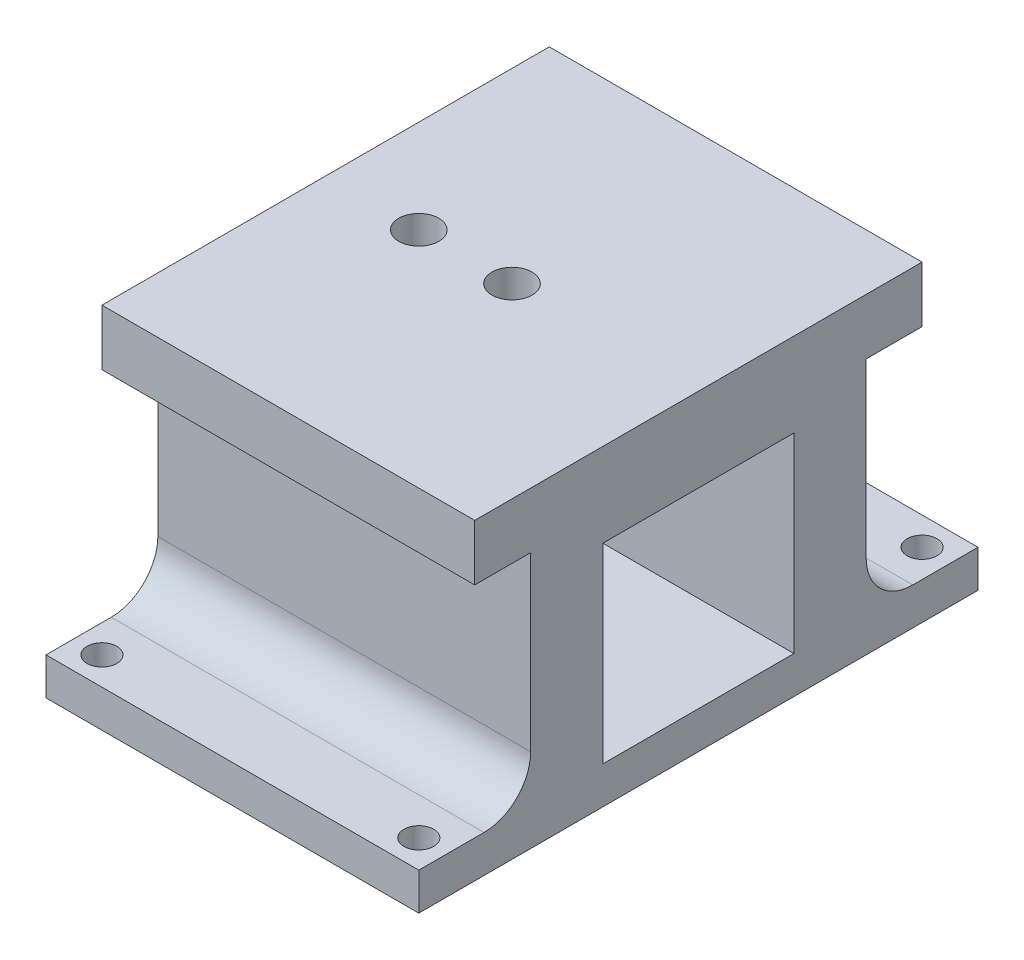
SolidWorks part; units mm, degrees
ref_plane "前视基准面" through (0, 0, 0) normal (0, 0, 1) x (1, 0, 0)
ref_plane "上视基准面" through (0, 0, 0) normal (0, 1, 0) x (1, 0, 0)
ref_plane "右视基准面" through (0, 0, 0) normal (1, 0, 0) x (0, 0, -1)
other "Configuration Table"
sketch "草图1" plane through (0, 0, 0) normal (0, 1, 0) x (1, 0, 0)
  line L0 (0, 0) -> (0, 14)
  line L1 (-20, -24) -> (20, -24)
  line L2 (-20, -24) -> (-20, 24)
  line L3 (-20, 24) -> (20, 24)
  line L4 (20, -24) -> (20, 24)
  line L5 (-20, -24) -> (20, 24) construction
  line L6 (-20, 24) -> (20, -24) construction
  line L7 (0, 14) -> (11.45, 14)
  line L8 (0, 0) -> (10.1755, 0)
  line L9 (0, 0) -> (0, -15.5)
  line L10 (0, -15.5) -> (0, 15.5) construction
  line L11 (-2.45, -15.5) -> (-2.45, 15.5)
  line L12 (2.45, -15.5) -> (2.45, 15.5)
  circle A0 centre (11.45, 14) radius 1.75
  circle A1 centre (-11.45, 14) radius 1.75
  circle A2 centre (-11.45, -14) radius 1.75
  circle A3 centre (11.45, -14) radius 1.75
  arc A4 (-2.45, -15.5) -> (2.45, -15.5) centre (0, -15.5) ccw
  arc A5 (2.45, 15.5) -> (-2.45, 15.5) centre (0, 15.5) ccw
  point P0 (0, 0)
  point P17 (0, 0)
  dimension "D5" = 3.5
  dimension "D8" = 2.45
  dimension "D1" = 48
  dimension "D2" = 40
  dimension "D3" = 14
  dimension "D4" = 11.45
  dimension "D6" = 15.5
  dimension "D7" = 31
extrude "凸台-拉伸1" add sketch "草图1" along normal blind 4
sketch "草图2" plane through (0, 4, 0) normal (0, 1, 0) x (1, 0, 0)
  line L0 (20, -24) -> (20, 24) construction
  line L1 (-20, -10.25) -> (20, -10.25)
  line L2 (-20, -10.25) -> (-20, 10.25)
  line L3 (-20, 10.25) -> (20, 10.25)
  line L4 (20, -10.25) -> (20, 10.25)
  line L5 (-20, -10.25) -> (20, 10.25) construction
  line L6 (-20, 10.25) -> (20, -10.25) construction
  line L8 (-20, -18) -> (20, -18)
  line L9 (-20, -18) -> (-20, 18)
  line L10 (-20, 18) -> (20, 18)
  line L11 (20, -18) -> (20, 18)
  line L12 (-20, -18) -> (20, 18) construction
  line L13 (-20, 18) -> (20, -18) construction
  point P0 (0, 0)
  point P8 (0, 0)
  dimension "D1" = 20.5
  dimension "D2" = 36
extrude "凸台-拉伸5" add sketch "草图2" along normal blind 20.5
sketch "草图4" plane through (0, 24.5, 0) normal (0, 1, 0) x (1, 0, 0)
  line L1 (-20, 18) -> (20, 18)
  line L2 (-20, 18) -> (-20, -18)
  line L3 (-20, -18) -> (20, -18)
  line L4 (20, 18) -> (20, -18)
extrude "凸台-拉伸6" add sketch "草图4" along normal blind 3
fillet "圆角4" radius 5 1 edges at (0, 4, -18)
fillet "圆角11" radius 5 1 edges at (0, 4, 18)
sketch "草图8" plane through (0, 27.5, 0) normal (0, 1, 0) x (1, 0, 0)
  line L1 (-20, 24) -> (20, 24)
  line L2 (-20, 24) -> (-20, -24)
  line L3 (-20, -24) -> (20, -24)
  line L4 (20, 24) -> (20, -24)
extrude "凸台-拉伸8" add sketch "草图8" along normal blind 4
sketch "草图9" plane through (0, 0, 0) normal (0, -1, 0) x (1, 0, 0)
  line L1 (-20, -30) -> (20, -30)
  line L2 (-20, -30) -> (-20, 30)
  line L3 (-20, 30) -> (20, 30)
  line L4 (20, -30) -> (20, 30)
  line L5 (-20, -30) -> (20, 30) construction
  line L6 (-20, 30) -> (20, -30) construction
  point P0 (0, 0)
  dimension "D1" = 60
extrude "凸台-拉伸9" add sketch "草图9" against normal blind 4
sketch "草图10" plane through (0, 4, 0) normal (0, 1, 0) x (1, 0, 0)
  line L0 (-1000, 0) -> (49000, 0) construction
  line L1 (-20, 30) -> (-17, 30)
  line L2 (-20, 30) -> (-20, 27)
  line L3 (-20, 27) -> (-17, 27)
  line L4 (-17, 30) -> (-17, 27)
  line L5 (0, -1000) -> (0, 49000) construction
  circle A0 centre (-17, 27) radius 1.6
  circle A1 centre (17, 27) radius 1.6
  circle A2 centre (17, -27) radius 1.6
  circle A3 centre (-17, -27) radius 1.6
  dimension "D3" = 3.2
  dimension "D1" = 3
  dimension "D2" = 3
extrude "切除-拉伸1" cut sketch "草图10" against normal through all contours A1 | A3 | A2 | A0
sketch "草图12" plane through (0, 31.5, 0) normal (0, 1, 0) x (1, 0, 0)
  line L1 (-20, 24) -> (20, 24)
  line L2 (-20, 24) -> (-20, -24)
  line L3 (-20, -24) -> (20, -24)
  line L4 (20, 24) -> (20, -24)
extrude "凸台-拉伸11" add sketch "草图12" along normal blind 2
sketch "草图13" plane through (0, 33.5, 0) normal (0, 1, 0) x (1, 0, 0)
  line L0 (-20, 0) -> (-10, 0)
  line L1 (-20, 24) -> (-20, -24) construction
  line L2 (-10, 0) -> (0, 0)
  circle A0 centre (-10, 0) radius 2.15
  circle A1 centre (0, 0) radius 2.15
  dimension "D2" = 4.3
  dimension "D4" = 4.3
  dimension "D1" = 10
  dimension "D3" = 10
extrude "切除-拉伸2" cut sketch "草图13" against normal through all
